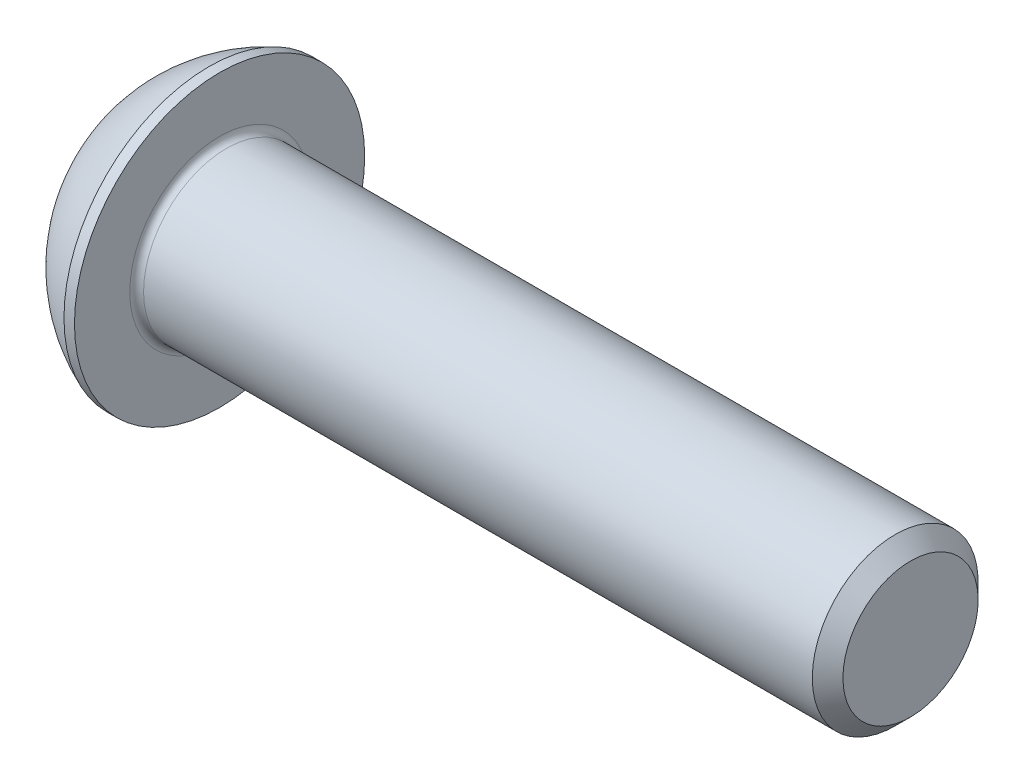
SolidWorks part; units mm, degrees
material "AISI Type A2 Tool Steel"
ref_plane "Plane1" through (0, 0, 0) normal (0, 0, 1) x (1, 0, 0)
ref_plane "Plane2" through (0, 0, 0) normal (0, 1, 0) x (1, 0, 0)
ref_plane "Plane3" through (0, 0, 0) normal (1, 0, 0) x (0, 0, -1)
sketch "BodySke" plane through (0, 0, 0) normal (0, 0, 1) x (1, 0, 0)
  line L0 (28.3, 0) -> (28.3, 2.4455)
  line L1 (27.7455, 3) -> (3.3, 3)
  line L2 (3.3, 3) -> (3.3, 5.25)
  line L3 (3.3, 5.25) -> (2.92, 5.25)
  line L4 (0, 0) -> (101.6, 0) construction
  line L5 (3.3, -5.25) -> (2.92, -5.25) construction
  line L6 (55.6768, -3) -> (3.3, -3) construction
  line L7 (28.3, 0) -> (0, 0)
  line L8 (0, 2.625) -> (0, -2.625) construction
  line L9 (0, 0) -> (0, 2.625)
  line L10 (28.3, 2.4455) -> (27.7455, 3)
  line L11 (28.3, -2.4455) -> (27.7455, -3) construction
  line L12 (4.3, 9.525) -> (4.3, -3) construction
  line L13 (3.3, 9.525) -> (3.3, -3) construction
  arc A1 (0, 2.625) -> (2.92, 5.25) centre (4.9997, 0) cw
  dimension "D1" = 5.25
  dimension "Diameter" = 6
  dimension "Length" = 25
  dimension "Head_dia" = 10.5
  dimension "Head_ht" = 3.3
  dimension "Head_side_ht" = 0.38
  dimension "Minor_dia" = 4.891
  dimension "Body_ch_ang" = 45
  dimension "Advance" = 1
  dimension "Thread_nom" = 25
revolve "BaseBody" add sketch "BodySke" angle 360 about L4
cosmetic thread "ThreadCosmetic" [suppressed] parameters "Thread_length"=23, "Thread_minor"=4.891
fillet "Fillet1" radius 0.25 1 edges at (3.3, 0, 3)
sketch "Sketch2" plane through (0, 0, 0) normal (0, 0, 1) x (1, 0, 0)
  line L0 (0, 2) -> (2.08, 2)
  line L1 (2.08, 2) -> (3.2347, 0)
  line L3 (3.2347, 0) -> (0, 0)
  line L4 (0, 0) -> (0, 2)
  line L5 (0, -2) -> (2.08, -2) construction
  line L6 (0, 0) -> (47.625, 0) construction
  dimension "D2" = 60
  dimension "PreBroach_depth" = 2.08
  dimension "PreBroach_dia" = 4
revolve "PreBroach" cut sketch "Sketch2" angle 360 about L6
sketch "Sketch3" plane through (0, 0, 0) normal (1, 0, 0) x (0, 0, -1)
  line L0 (-2, -1.1547) -> (-2, 1.1547)
  line L1 (-2, 1.1547) -> (0, 2.3094)
  line L2 (0, 2.3094) -> (2, 1.1547)
  line L3 (2, 1.1547) -> (2, -1.1547)
  line L4 (2, -1.1547) -> (0, -2.3094)
  line L5 (0, -2.3094) -> (-2, -1.1547)
  dimension "D1" = 2
  dimension "D2" = 2
  dimension "D3" = 4
  dimension "Hex_size" = 4
extrude "Hex" cut sketch "Sketch3" along normal blind 2.08
sketch "ThdSchSke" [suppressed] plane through (0, 0, 0) normal (0, 0, 1) x (1, 0, 0)
  line L0 (12.8, -6.8985) -> (12.0287, -8)
  line L1 (12.8, -6.8985) -> (13.5713, -8)
  line L2 (13.5713, -8) -> (13.5713, -10)
  line L3 (-3.175, 0) -> (5.1513, 0) construction
  line L5 (13.5713, -10) -> (12.0287, -10)
  line L6 (12.0287, -10) -> (12.0287, -8)
  dimension "Thread_minor" = 4.891
  dimension "Diameter" = 6
  dimension "Start" = 5.3
  dimension "SideAngle" = 55
  dimension "VeeAngle" = 70
  dimension "Overcut" = 7.5
revolve "ThreadSchematic" [suppressed] cut sketch "ThdSchSke" angle 360 about L3
pattern_linear "ThdSchPat" [suppressed]
equation "\"D1@BodySke\" = \"Head_dia@BodySke\" * .5"
equation "\"Thread_minor@ThreadCosmetic\" = \"Minor_dia@BodySke\""
equation "\"D1@Sketch3\" = \"Hex_size@Sketch3\" / 2"
equation "\"D2@Sketch3\" = \"D1@Sketch3\""
equation "\"D3@Sketch3\" = \"Hex_size@Sketch3\""
equation "\"Thread_length@ThreadCosmetic\" = ((sgn( (\"Length@BodySke\" - \"Advance@BodySke\" * 2.0) - \"Thread_nom@BodySke\" )-1)*( (\"Length@BodySke\" - \"Advance@BodySke\" * 2.0) - \"Thread_nom@BodySke\" ))/-2+ \"Thread_nom@BodySke\""
equation "\"Thread_minor@ThdSchSke\" = \"Minor_dia@BodySke\""
equation "\"Diameter@ThdSchSke\" = \"Diameter@BodySke\""
equation "\"Overcut@ThdSchSke\" = \"Diameter@BodySke\" * 1.25"
equation "\"Start@ThdSchSke\" = \"Head_ht@BodySke\" + \"Length@BodySke\" - \"Thread_length@ThreadCosmetic\"  '---Non-countersunk---"
equation "\"Num_threads@ThdSchPat\" = int( \"Thread_length@ThreadCosmetic\" / \"Advance@BodySke\" + 0.999 )  + 1"
equation "\"Advance@ThdSchPat\" = \"Thread_length@ThreadCosmetic\" /  (\"Num_threads@ThdSchPat\" - 1) 'relax it"
equation "\"Num_threads@ThdSchPat\" = \"Num_threads@ThdSchPat\" - sgn( \"Num_threads@ThdSchPat\" - 1) '---chamfered tips only---"
